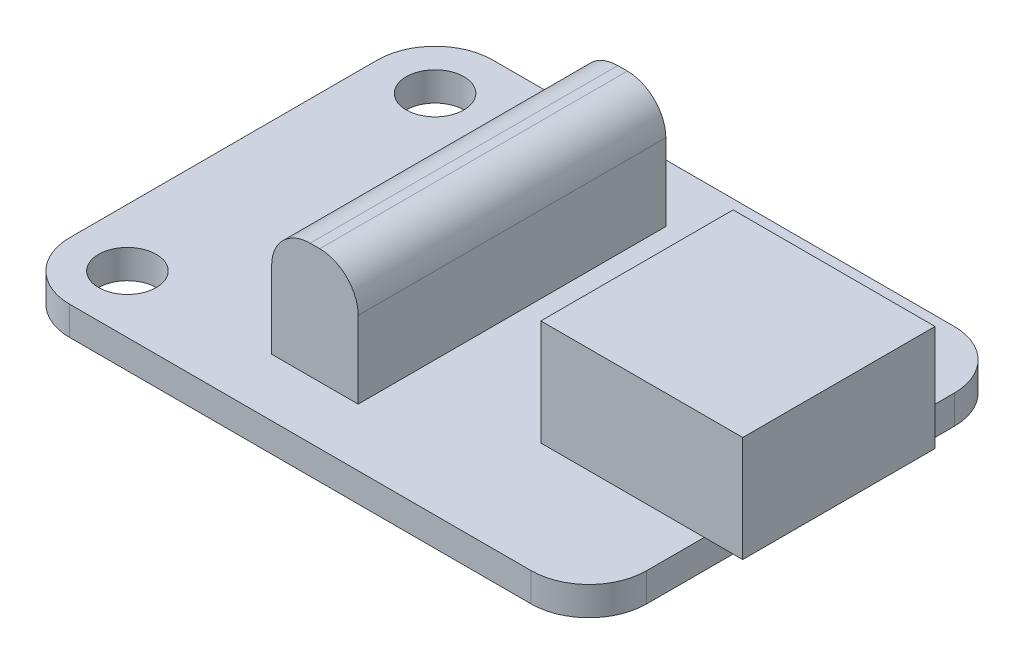
SolidWorks part; units mm, degrees
ref_plane "Спереди" through (0, 0, 0) normal (0, 0, 1) x (1, 0, 0)
ref_plane "Сверху" through (0, 0, 0) normal (0, 1, 0) x (1, 0, 0)
ref_plane "Справа" through (0, 0, 0) normal (1, 0, 0) x (0, 0, -1)
sketch "Эскиз1" plane through (0, 0, 0) normal (0, 1, 0) x (1, 0, 0)
  line L0 (-28.1983, 2.8346) -> (-28.1983, -13.1654)
  line L1 (-25.1983, 5.8346) -> (-1.1983, 5.8346)
  line L2 (1.8017, 2.8346) -> (1.8017, -13.1654)
  line L3 (-1.1983, -16.1654) -> (-25.1983, -16.1654)
  arc A0 (1.8017, -13.1654) -> (-1.1983, -16.1654) centre (-1.1983, -13.1654) cw
  arc A1 (-25.1983, -16.1654) -> (-28.1983, -13.1654) centre (-25.1983, -13.1654) cw
  arc A2 (-25.1983, 5.8346) -> (-28.1983, 2.8346) centre (-25.1983, 2.8346) ccw
  arc A3 (1.8017, 2.8346) -> (-1.1983, 5.8346) centre (-1.1983, 2.8346) ccw
  circle A4 centre (-25.1983, -13.1654) radius 1.5
  circle A5 centre (-25.1983, 2.8346) radius 1.5
  point P8 (-28.1983, -16.1654)
  point P11 (-28.1983, 5.8346)
  point P14 (1.8017, 5.8346)
  dimension "D3" = 3
  dimension "D1" = 22
  dimension "D2" = 30
extrude "Бобышка-Вытянуть1" add sketch "Эскиз1" along normal blind 1.5
sketch "Эскиз2" plane through (0, 1.5, 0) normal (0, 1, 0) x (1, 0, 0)
  line L0 (1.8017, -5.1654) -> (-6.6983, -5.1654) construction
  line L2 (1.8017, -13.1654) -> (1.8017, 2.8346) construction
  line L3 (1.8017, -0.1654) -> (-6.6983, -0.1654)
  line L4 (1.8017, -10.1654) -> (-6.6983, -10.1654)
  line L5 (-6.6983, -0.1654) -> (-6.6983, -10.1654)
  line L6 (1.8017, -10.1654) -> (3.8017, -10.1654)
  line L7 (3.8017, -10.1654) -> (3.8017, -0.1654)
  line L8 (3.8017, -0.1654) -> (1.8017, -0.1654)
  dimension "D1" = 5
  dimension "D2" = 5
extrude "Бобышка-Вытянуть2" add sketch "Эскиз2" along normal blind 5.5
sketch "Эскиз3" plane through (0, 1.5, 0) normal (0, 1, 0) x (1, 0, 0)
  line L0 (-28.1983, -5.1654) -> (-13.1983, -5.1654) construction
  line L1 (-28.1983, 2.8346) -> (-28.1983, -13.1654) construction
  line L2 (-25.1983, 2.8346) -> (-13.1983, 2.8346) construction
  line L3 (-25.1983, -13.1654) -> (-13.1983, -13.1654) construction
  line L4 (-13.1983, -13.1654) -> (-13.1983, 2.8346)
  line L5 (-13.1983, 2.8346) -> (-17.6983, 2.8346)
  line L6 (-17.6983, 2.8346) -> (-17.6983, -13.1654)
  line L7 (-17.6983, -13.1654) -> (-13.1983, -13.1654)
extrude "Бобышка-Вытянуть3" add sketch "Эскиз3" along normal blind 6
fillet "Скругление1" radius 2 2 edges at (-17.6983, 7.5, 5.1654) (-13.1983, 7.5, 5.1654)
